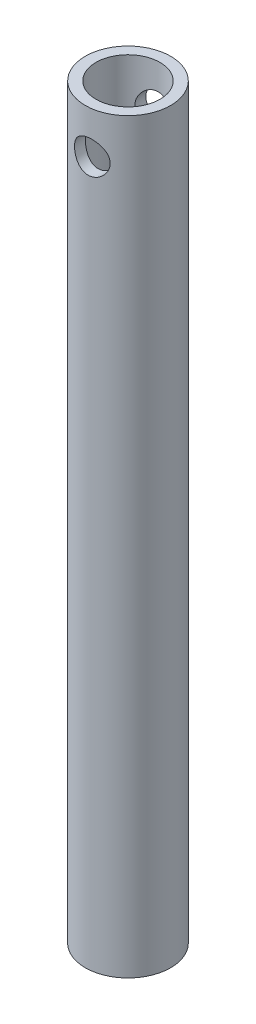
SolidWorks part; units mm, degrees
material "尼龙 101"
ref_plane "前视基准面" through (0, 0, 0) normal (0, 0, 1) x (1, 0, 0)
ref_plane "上视基准面" through (0, 0, 0) normal (0, 1, 0) x (1, 0, 0)
ref_plane "右视基准面" through (0, 0, 0) normal (1, 0, 0) x (0, 0, -1)
sketch "草图1" plane through (0, 0, 0) normal (0, 1, 0) x (1, 0, 0)
  circle A0 centre (0, 0) radius 4
  circle A1 centre (0, 0) radius 3
  dimension "D1" = 6
  dimension "D2" = 8
extrude "凸台-拉伸1" add sketch "草图1" along normal blind 70
sketch "草图2" plane through (0.1102, 0, 1.1949) normal (0.0918, 0, 0.9958) x (0.9958, 0, -0.0918)
  circle A0 centre (0, 66) radius 1.5363
  arc A1 (0.9, 64.755) -> (0.9, 67.245) centre (0, 66) ccw construction
extrude "切除-拉伸1" cut sketch "草图2" against normal through all both and the other way through all
